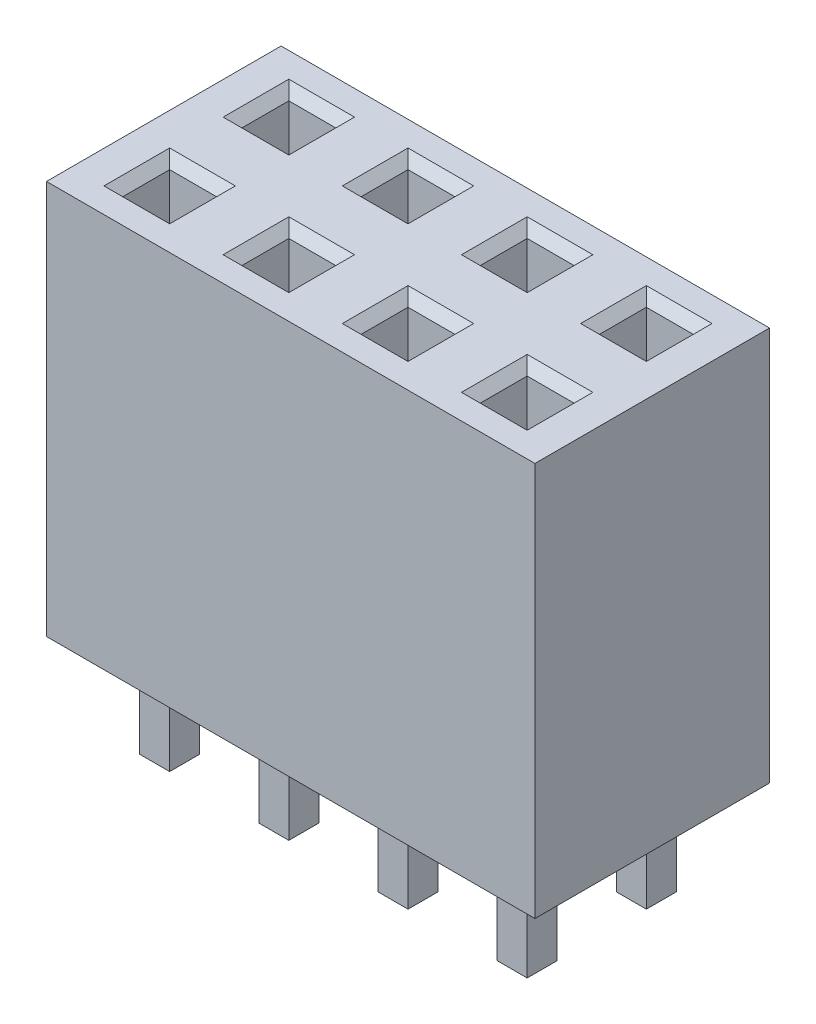
SolidWorks part; units mm, degrees
material "C (Графит)"
ref_plane "Спереди" through (0, 0, 0) normal (0, 0, 1) x (1, 0, 0)
ref_plane "Сверху" through (0, 0, 0) normal (0, 1, 0) x (1, 0, 0)
ref_plane "Справа" through (0, 0, 0) normal (1, 0, 0) x (0, 0, -1)
sketch "Эскиз1" plane through (0, 0, 0) normal (0, 1, 0) x (1, 0, 0)
  line L1 (-1.395, -2.5) -> (1.395, -2.5)
  line L2 (-1.395, -2.5) -> (-1.395, 2.5)
  line L3 (-1.395, 2.5) -> (1.395, 2.5)
  line L4 (1.395, -2.5) -> (1.395, 2.5)
  line L5 (-1.395, -2.5) -> (1.395, 2.5) construction
  line L6 (-1.395, 2.5) -> (1.395, -2.5) construction
  point P0 (0, 0)
  dimension "D1" = 5
  dimension "D2" = 2.79
extrude "Бобышка-Вытянуть1" add sketch "Эскиз1" along normal blind 8.4
sketch "Эскиз2" plane through (0, 8.4, 0) normal (0, 1, 0) x (1, 0, 0)
  line L0 (-1.395, 2.5) -> (-1.395, -2.5) construction
  line L1 (-0.5, 1.77) -> (0.5, 1.77)
  line L2 (-0.5, 1.77) -> (-0.5, 0.77)
  line L3 (-0.5, 0.77) -> (0.5, 0.77)
  line L4 (0.5, 1.77) -> (0.5, 0.77)
  line L5 (-0.5, 1.77) -> (0.5, 0.77) construction
  line L6 (-0.5, 0.77) -> (0.5, 1.77) construction
  line L7 (-1.395, 0) -> (-29.5201, 0) construction
  line L8 (0.5, -1.77) -> (0.5, -0.77)
  line L9 (-0.5, -0.77) -> (0.5, -0.77)
  line L10 (-0.5, -1.77) -> (-0.5, -0.77)
  line L11 (-0.5, -1.77) -> (0.5, -1.77)
  point P0 (0, 1.27)
  dimension "D1" = 1
  dimension "D2" = 1
  dimension "D3" = 1.395
  dimension "D4" = 1.27
extrude "Вырез-Вытянуть1" cut sketch "Эскиз2" against normal blind 8
chamfer "Фаска1" distance 0.2 angle 45 8 edges at (0.5, 8.4, -1.27) (0, 8.4, -0.77) (-0.5, 8.4, -1.27) (0, 8.4, -1.77) (0, 8.4, 1.77) (-0.5, 8.4, 1.27) (0, 8.4, 0.77) (0.5, 8.4, 1.27)
sketch "Эскиз3" plane through (0, 0, 0) normal (0, -1, 0) x (-1, 0, 0)
  line L0 (1.395, 2.5) -> (1.395, -2.5) construction
  line L1 (0.32, 0.95) -> (-0.32, 0.95)
  line L2 (0.32, 0.95) -> (0.32, 1.59)
  line L3 (0.32, 1.59) -> (-0.32, 1.59)
  line L4 (-0.32, 0.95) -> (-0.32, 1.59)
  line L5 (0.32, 0.95) -> (-0.32, 1.59) construction
  line L6 (0.32, 1.59) -> (-0.32, 0.95) construction
  line L7 (1.395, 0) -> (32.9327, 0) construction
  line L8 (0.32, -0.95) -> (-0.32, -0.95)
  line L9 (-0.32, -0.95) -> (-0.32, -1.59)
  line L10 (0.32, -1.59) -> (-0.32, -1.59)
  line L11 (0.32, -0.95) -> (0.32, -1.59)
  point P0 (0, 1.27)
  dimension "D1" = 0.64
  dimension "D2" = 0.64
  dimension "D3" = 1.395
  dimension "D4" = 2.54
extrude "Бобышка-Вытянуть2" add sketch "Эскиз3" along normal blind 2.29
chamfer "Фаска2" distance 0.2 angle 45 8 edges at (0, -2.29, -1.59) (-0.32, -2.29, -1.27) (0, -2.29, -0.95) (0.32, -2.29, -1.27) (0, -2.29, 1.59) (0.32, -2.29, 1.27) (0, -2.29, 0.95) (-0.32, -2.29, 1.27)
pattern_linear "Линейный массив1" count 4 spacing 2.54 along (1, 0, 0) of "Бобышка-Вытянуть1", "Вырез-Вытянуть1", "Фаска1", "Бобышка-Вытянуть2", "Фаска2"
